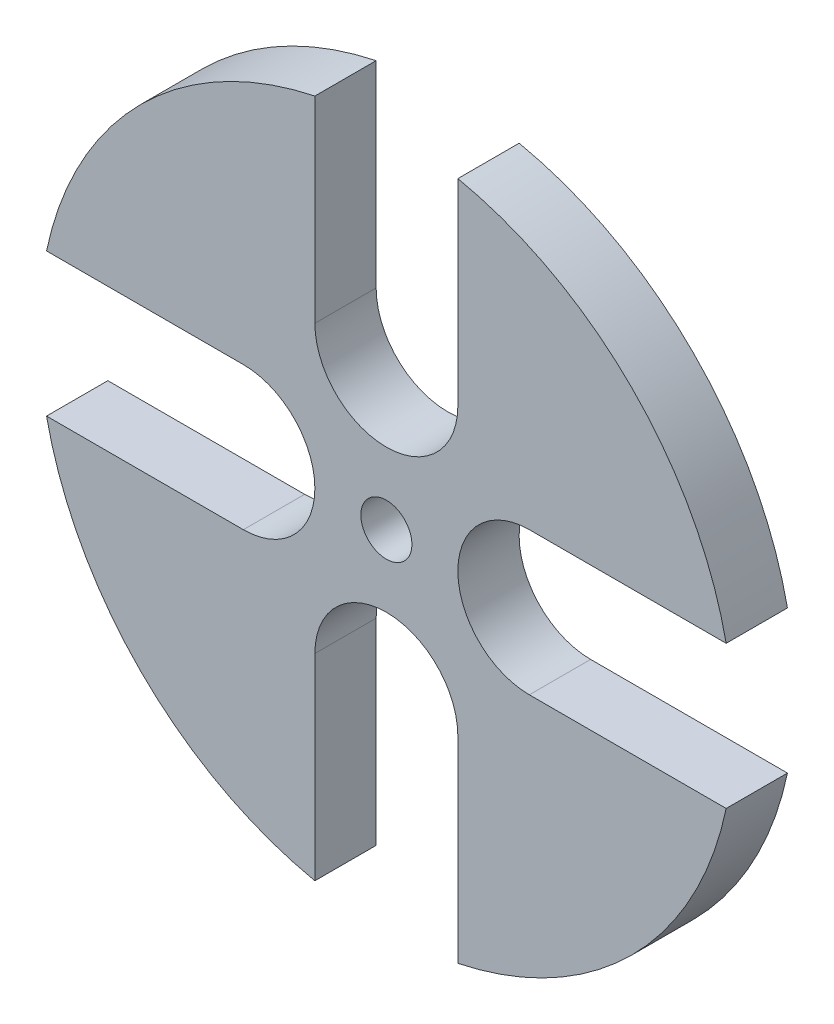
SolidWorks part; units mm, degrees
ref_plane "前视基准面" through (0, 0, 0) normal (0, 0, 1) x (1, 0, 0)
ref_plane "上视基准面" through (0, 0, 0) normal (0, 1, 0) x (1, 0, 0)
ref_plane "右视基准面" through (0, 0, 0) normal (1, 0, 0) x (0, 0, -1)
sketch "草图1" plane through (0, 0, 0) normal (0, 0, 1) x (1, 0, 0)
  line L0 (-3.5, 7) -> (-3.5, 16.6358)
  line L1 (3.5, 7) -> (3.5, 16.6358)
  line L2 (7, 3.5) -> (16.6358, 3.5)
  line L3 (7, -3.5) -> (16.6358, -3.5)
  line L4 (-3.5, -7) -> (-3.5, -16.6358)
  line L5 (3.5, -7) -> (3.5, -16.6358)
  line L6 (-7, -3.5) -> (-16.6358, -3.5)
  line L7 (-7, 3.5) -> (-16.6358, 3.5)
  circle A0 centre (0, 0) radius 17
  circle A1 centre (7, 0) radius 3.5
  circle A2 centre (0, 7) radius 3.5
  circle A3 centre (-7, 0) radius 3.5
  circle A4 centre (0, -7) radius 3.5
  circle A5 centre (0, 0) radius 1.25
extrude "凸台-拉伸1" add sketch "草图1" along normal blind 3 contours A4 L5 A0 L3 A1 L2 L1 A2 L0 L7 A3 L6 L4 A5
